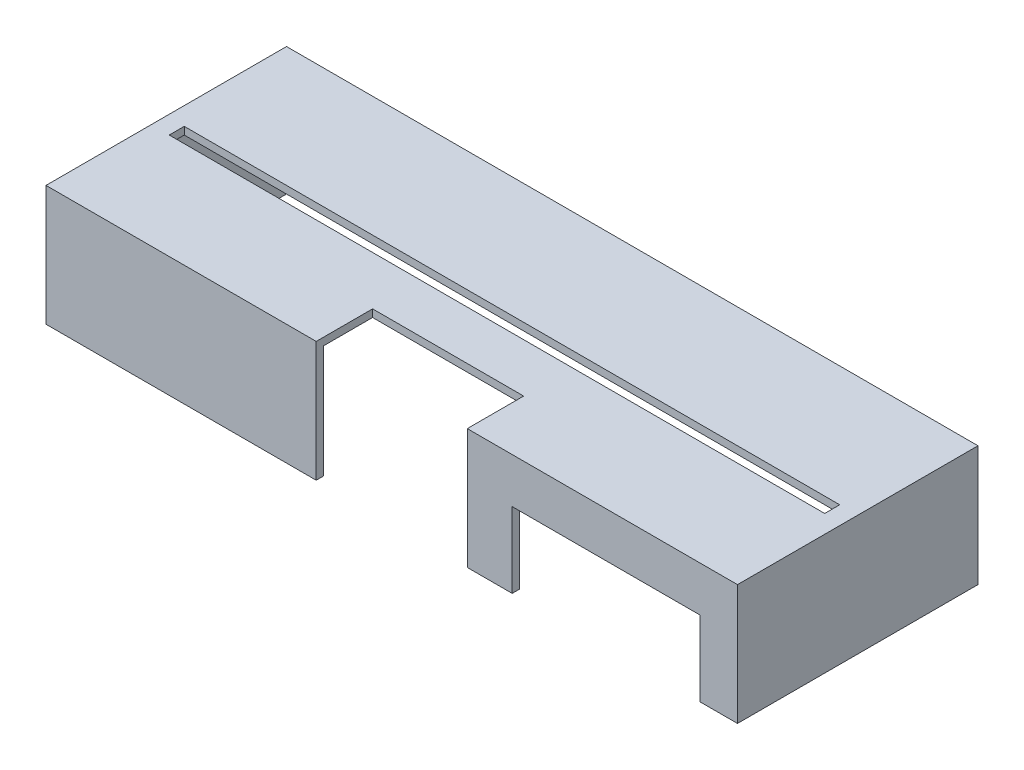
SolidWorks part; units mm, degrees
ref_plane "Front Plane" through (0, 0, 0) normal (0, 0, 1) x (1, 0, 0)
ref_plane "Top Plane" through (0, 0, 0) normal (0, 1, 0) x (1, 0, 0)
ref_plane "Right Plane" through (0, 0, 0) normal (1, 0, 0) x (0, 0, -1)
sketch "Sketch1" plane through (0, 0, 0) normal (0, 1, 0) x (1, 0, 0)
  line L1 (-90, 30) -> (90, 30)
  line L2 (-90, 30) -> (-90, -30)
  line L3 (-90, -30) -> (90, -30)
  line L4 (90, 30) -> (90, -30)
  line L5 (-90, 30) -> (90, -30) construction
  line L6 (-90, -30) -> (90, 30) construction
  point P0 (0, 0)
  dimension "D1" = 60
  dimension "D2" = 180
extrude "Extrude-Thin1" add sketch "Sketch1" along normal blind 30 thin thin type one direction wall 2
sketch "Sketch3" plane through (0, 30, 0) normal (0, 1, 0) x (1, 0, 0)
  line L0 (-92, -32) -> (92, -32) construction
  line L1 (-92, 32) -> (92, 32)
  line L2 (-92, 32) -> (-92, -32)
  line L3 (-92, -32) -> (92, -32)
  line L4 (92, 32) -> (92, -32)
extrude "Boss-Extrude1" add sketch "Sketch3" along normal blind 2
sketch "Sketch4" plane through (0, 32, 0) normal (0, 1, 0) x (1, 0, 0)
  line L0 (-92, 32) -> (-92, -32) construction
  line L1 (-92, -32) -> (-92, 0) construction
  line L2 (-92, 0) -> (-92, -16) construction
  line L3 (-92, -16) -> (-92, -8) construction
  line L4 (-92, -8) -> (92, -8) construction
  line L5 (92, -32) -> (92, 32) construction
  line L6 (92, -8) -> (-92, -8) construction
  line L7 (-92, -8) -> (-92, 0) construction
  line L8 (-92, 0) -> (92, 0) construction
  line L9 (92, 0) -> (92, -8) construction
  line L10 (92, -8) -> (92, -4) construction
  line L11 (92, -4) -> (92, 0) construction
  line L12 (92, 0) -> (92, -2) construction
  line L13 (92, -2) -> (-92, -2) construction
  line L14 (-92, -2) -> (-92, -4) construction
  line L15 (-92, -4) -> (92, -4) construction
  line L17 (-87.2097, 0) -> (87.2097, 0)
  line L18 (-87.2097, 0) -> (-87.2097, -4)
  line L19 (-87.2097, -4) -> (87.2097, -4)
  line L20 (87.2097, 0) -> (87.2097, -4)
  line L21 (-87.2097, 0) -> (87.2097, -4) construction
  line L22 (-87.2097, -4) -> (87.2097, 0) construction
  point P4 (0, -2)
extrude "Cut-Extrude1" cut sketch "Sketch4" against normal blind 5
sketch "Sketch5" plane through (0, 0, 32) normal (0, 0, 1) x (1, 0, 0)
  line L0 (0, 32) -> (0, 0) construction
  line L1 (-92, 32) -> (92, 32) construction
  line L3 (-20.0979, 45.5348) -> (20.0979, 45.5348)
  line L4 (-20.0979, 45.5348) -> (-20.0979, -13.5348)
  line L5 (-20.0979, -13.5348) -> (20.0979, -13.5348)
  line L6 (20.0979, 45.5348) -> (20.0979, -13.5348)
  line L7 (-20.0979, 45.5348) -> (20.0979, -13.5348) construction
  line L8 (-20.0979, -13.5348) -> (20.0979, 45.5348) construction
  point P5 (0, 16)
extrude "Cut-Extrude2" cut sketch "Sketch5" against normal blind 15
sketch "Sketch6" plane through (0, 0, 32) normal (0, 0, 1) x (1, 0, 0)
  line L1 (-20.0979, 63.7769) -> (20.0979, 63.7769)
  line L2 (-20.0979, 63.7769) -> (-20.0979, 0)
  line L3 (-20.0979, 0) -> (20.0979, 0)
  line L4 (20.0979, 63.7769) -> (20.0979, 0)
extrude "Extrude-Thin2" add sketch "Sketch6" along normal blind 35 and the other way up to surface thin other way up to face at (0, 31, 17) thin type one direction wall 2
sketch "Sketch7" plane through (0, 0, 0) normal (0, -1, 0) x (1, 0, 0)
  line L1 (-61.6448, 15.0511) -> (66.3737, 15.0511)
  line L2 (-61.6448, 15.0511) -> (-61.6448, 73.6559)
  line L3 (-61.6448, 73.6559) -> (66.3737, 73.6559)
  line L4 (66.3737, 15.0511) -> (66.3737, 73.6559)
extrude "Cut-Extrude3" cut sketch "Sketch7" along normal blind 85
sketch "Sketch8" plane through (-22.0979, 0, 0) normal (-1, 0, 0) x (0, 0, 1)
  line L1 (17, 30) -> (30, 30)
  line L2 (17, 30) -> (17, 0)
  line L3 (17, 0) -> (30, 0)
  line L4 (30, 30) -> (30, 0)
extrude "Cut-Extrude4" cut sketch "Sketch8" against normal blind 85
sketch "Sketch9" plane through (0, 0, 67) normal (0, 0, 1) x (1, 0, 0)
  line L0 (-22.0979, 65.7769) -> (-22.0979, 0) construction
  line L1 (-22.0979, 65.7769) -> (22.0979, 65.7769)
  line L2 (-22.0979, 65.7769) -> (-22.0979, 0)
  line L3 (-22.0979, 0) -> (22.0979, 0)
  line L4 (22.0979, 65.7769) -> (22.0979, 0)
  line L5 (22.0979, 65.7769) -> (-22.0979, 65.7769) construction
extrude "Boss-Extrude2" add sketch "Sketch9" along normal blind 2
sketch "Sketch13" plane through (0, 0, 69) normal (0, 0, 1) x (1, 0, 0)
  line L0 (0, 50.7769) -> (0, 10.7769) construction
  line L1 (22.0979, 65.7769) -> (-22.0979, 65.7769) construction
  line L3 (0, 65.7769) -> (0, 50.7769) construction
  line L4 (-10.03, 50.8069) -> (10.03, 50.8069)
  line L5 (-10.03, 50.8069) -> (-10.03, 10.7469)
  line L6 (-10.03, 10.7469) -> (10.03, 10.7469)
  line L7 (10.03, 50.8069) -> (10.03, 10.7469)
  line L8 (-10.03, 50.8069) -> (10.03, 10.7469) construction
  line L9 (-10.03, 10.7469) -> (10.03, 50.8069) construction
  point P1 (0, 30.7769)
  dimension "D1" = 15
  dimension "D2" = 40
  dimension "D3" = 20.06
  dimension "D4" = 40.06
extrude "Cut-Extrude6" cut sketch "Sketch13" against normal blind 10
sketch "Sketch18" plane through (0, 0, 69) normal (0, 0, 1) x (1, 0, 0)
  line L0 (0, 10.7469) -> (0, 0) construction
  line L1 (-10.03, 10.7469) -> (10.03, 10.7469) construction
  line L2 (0, 0) -> (0, 10.7469) construction
  line L3 (0, 10.7469) -> (0, 6.2469) construction
  line L4 (0, 6.2469) -> (-5, 6.2469) construction
  line L5 (0, 6.2469) -> (5, 6.2469) construction
  circle A0 centre (-5, 6.2469) radius 2.03
  circle A1 centre (5, 6.2469) radius 2.03
  dimension "D4" = 4.06
  dimension "D5" = 4.06
  dimension "D1" = 4.5
  dimension "D2" = 5
  dimension "D3" = 5
extrude "Cut-Extrude8" cut sketch "Sketch18" against normal blind 10
sketch "Sketch19" plane through (0, 0, 32) normal (0, 0, 1) x (1, 0, 0)
  line L0 (92, 0) -> (22.0979, 0) construction
  line L2 (32.0489, 20) -> (82.0489, 20)
  line L3 (32.0489, 20) -> (32.0489, -20)
  line L4 (32.0489, -20) -> (82.0489, -20)
  line L5 (82.0489, 20) -> (82.0489, -20)
  line L6 (32.0489, 20) -> (82.0489, -20) construction
  line L7 (32.0489, -20) -> (82.0489, 20) construction
  point P4 (57.0489, 0)
  dimension "D1" = 50
  dimension "D2" = 40
extrude "Cut-Extrude9" cut sketch "Sketch19" against normal blind 10
sketch "Sketch20" plane through (0, 0, 69) normal (0, 0, 1) x (1, 0, 0)
  line L0 (-10.03, 50.8069) -> (10.03, 50.8069) construction
  line L1 (10.03, 50.8069) -> (0, 50.8069) construction
  line L2 (0, 50.8069) -> (0, 55.3069) construction
  line L3 (0, 55.3069) -> (5, 55.3069) construction
  line L4 (0, 55.3069) -> (-5, 55.3069) construction
  circle A0 centre (-5, 55.3069) radius 2.03
  circle A1 centre (5, 55.3069) radius 2.03
  dimension "D4" = 4.06
  dimension "D5" = 4.06
  dimension "D1" = 4.5
  dimension "D2" = 5
  dimension "D3" = 5
extrude "Cut-Extrude10" cut sketch "Sketch20" against normal blind 10
sketch "Sketch21" plane through (-22.0979, 0, 0) normal (-1, 0, 0) x (0, 0, 1)
  line L1 (17, 32) -> (72.7329, 32)
  line L2 (17, 32) -> (17, 66.4943)
  line L3 (17, 66.4943) -> (72.7329, 66.4943)
  line L4 (72.7329, 32) -> (72.7329, 66.4943)
  line L5 (32, 32) -> (76.3484, 32)
  line L6 (32, 32) -> (32, -6.7433)
  line L7 (32, -6.7433) -> (76.3484, -6.7433)
  line L8 (76.3484, 32) -> (76.3484, -6.7433)
  line M1 (32, 0) -> (69, 0)
  line M2 (69, 0) -> (69, 65.7769)
  line M3 (69, 65.7769) -> (17, 65.7769)
  line M4 (17, 65.7769) -> (17, 32)
  line M5 (17, 32) -> (32, 32)
  line M6 (32, 32) -> (32, 0)
extrude "Cut-Extrude11" cut sketch "Sketch21" against normal blind 217 contours L8 L5 L1 L6 L7 M2 M1 | L1 M6 M1 M2 | L1 M5 M2 M3 M4
